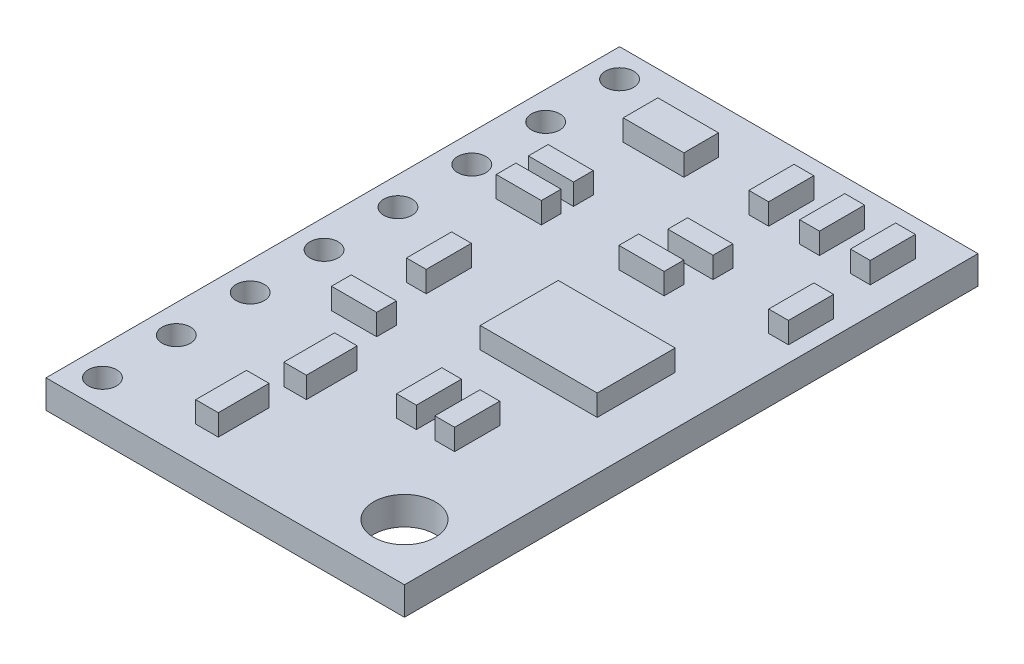
SolidWorks part; units mm, degrees
ref_plane "Front" through (0, 0, 0) normal (0, 0, 1) x (1, 0, 0)
ref_plane "Top" through (0, 0, 0) normal (0, 1, 0) x (1, 0, 0)
ref_plane "Right" through (0, 0, 0) normal (1, 0, 0) x (0, 0, -1)
sketch "Sketch1" plane through (0, 0, 0) normal (0, 1, 0) x (1, 0, 0)
  line L1 (0, 0) -> (12.7, 0)
  line L2 (0, 0) -> (0, 20.32)
  line L3 (0, 20.32) -> (12.7, 20.32)
  line L4 (12.7, 0) -> (12.7, 20.32)
extrude "Boss-Extrude1" add sketch "Sketch1" along normal blind 1
sketch "Sketch2" plane through (0, 1, 0) normal (0, 1, 0) x (1, 0, 0)
  circle A0 centre (1, 19.32) radius 0.5
  circle A1 centre (1, 16.7029) radius 0.5
  circle A2 centre (1, 14.0857) radius 0.5
  circle A3 centre (1, 11.4686) radius 0.5
  circle A4 centre (1, 8.8514) radius 0.5
  circle A5 centre (1, 6.2343) radius 0.5
  circle A6 centre (1, 3.6171) radius 0.5
  circle A7 centre (1, 1) radius 0.5
  circle A8 centre (10.7, 2) radius 1.0922
  dimension "D1" = 8
extrude "Cut-Extrude2" cut sketch "Sketch2" against normal blind 1
sketch "Sketch3" plane through (0, 1, 0) normal (0, 1, 0) x (1, 0, 0)
  line L0 (9.2502, 19.0518) -> (9.9502, 19.0518)
  line L1 (2.9983, 18.6799) -> (5.1475, 18.6799)
  line L2 (2.9983, 18.6799) -> (2.9983, 17.4518)
  line L3 (2.9983, 17.4518) -> (5.1475, 17.4518)
  line L4 (5.1475, 18.6799) -> (5.1475, 17.4518)
  line L5 (6.8361, 11.3113) -> (10.9809, 11.3113)
  line L6 (6.8361, 11.3113) -> (6.8361, 8.5481)
  line L7 (6.8361, 8.5481) -> (10.9809, 8.5481)
  line L8 (10.9809, 11.3113) -> (10.9809, 8.5481)
  line L9 (4.4823, 5.7428) -> (5.2823, 5.7428)
  line L10 (4.4823, 5.7428) -> (4.4823, 3.9428)
  line L11 (4.4823, 3.9428) -> (5.2823, 3.9428)
  line L12 (5.2823, 5.7428) -> (5.2823, 3.9428)
  line L13 (4.0729, 3.0308) -> (4.8729, 3.0308)
  line L14 (4.0729, 3.0308) -> (4.0729, 1.2308)
  line L15 (4.0729, 1.2308) -> (4.8729, 1.2308)
  line L16 (4.8729, 3.0308) -> (4.8729, 1.2308)
  line L17 (7.4502, 19.0518) -> (8.1502, 19.0518)
  line L18 (7.4502, 19.0518) -> (7.4502, 17.4518)
  line L19 (7.4502, 17.4518) -> (8.1502, 17.4518)
  line L20 (8.1502, 19.0518) -> (8.1502, 17.4518)
  line L21 (9.2502, 19.0518) -> (9.2502, 17.4518)
  line L22 (9.2502, 17.4518) -> (9.9502, 17.4518)
  line L23 (9.9502, 19.0518) -> (9.9502, 17.4518)
  line L24 (11.0502, 19.0518) -> (11.7502, 19.0518)
  line L25 (11.0502, 19.0518) -> (11.0502, 17.4518)
  line L26 (11.0502, 17.4518) -> (11.7502, 17.4518)
  line L27 (11.7502, 19.0518) -> (11.7502, 17.4518)
  line L28 (11.4415, 15.7632) -> (12.1415, 15.7632)
  line L29 (11.4415, 15.7632) -> (11.4415, 14.1632)
  line L30 (11.4415, 14.1632) -> (12.1415, 14.1632)
  line L31 (12.1415, 15.7632) -> (12.1415, 14.1632)
  line L32 (2.4866, 14.6026) -> (2.4866, 15.3026)
  line L33 (2.4866, 14.6026) -> (4.0866, 14.6026)
  line L34 (4.0866, 14.6026) -> (4.0866, 15.3026)
  line L35 (2.4866, 15.3026) -> (4.0866, 15.3026)
  line L36 (2.4866, 13.4632) -> (2.4866, 14.1632)
  line L37 (2.4866, 13.4632) -> (4.0866, 13.4632)
  line L38 (4.0866, 13.4632) -> (4.0866, 14.1632)
  line L39 (2.4866, 14.1632) -> (4.0866, 14.1632)
  line L40 (7.205, 14.8265) -> (7.205, 15.5265)
  line L41 (7.205, 14.8265) -> (8.805, 14.8265)
  line L42 (8.805, 14.8265) -> (8.805, 15.5265)
  line L43 (7.205, 15.5265) -> (8.805, 15.5265)
  line L44 (6.8361, 13.4632) -> (6.8361, 14.1632)
  line L45 (6.8361, 13.4632) -> (8.4361, 13.4632)
  line L46 (8.4361, 13.4632) -> (8.4361, 14.1632)
  line L47 (6.8361, 14.1632) -> (8.4361, 14.1632)
  line L48 (3.4584, 10.9126) -> (4.1584, 10.9126)
  line L49 (3.4584, 10.9126) -> (3.4584, 9.3126)
  line L50 (3.4584, 9.3126) -> (4.1584, 9.3126)
  line L51 (4.1584, 10.9126) -> (4.1584, 9.3126)
  line L52 (7.4502, 6.571) -> (8.1502, 6.571)
  line L53 (7.4502, 6.571) -> (7.4502, 4.971)
  line L54 (7.4502, 4.971) -> (8.1502, 4.971)
  line L55 (8.1502, 6.571) -> (8.1502, 4.971)
  line L56 (8.805, 6.571) -> (9.505, 6.571)
  line L57 (8.805, 6.571) -> (8.805, 4.971)
  line L58 (8.805, 4.971) -> (9.505, 4.971)
  line L59 (9.505, 6.571) -> (9.505, 4.971)
  line L60 (2.9983, 7.1162) -> (2.9983, 7.8162)
  line L61 (2.9983, 7.1162) -> (4.5983, 7.1162)
  line L62 (4.5983, 7.1162) -> (4.5983, 7.8162)
  line L63 (2.9983, 7.8162) -> (4.5983, 7.8162)
  dimension "D1" = 3
extrude "Boss-Extrude3" add sketch "Sketch3" along normal blind 0.75
